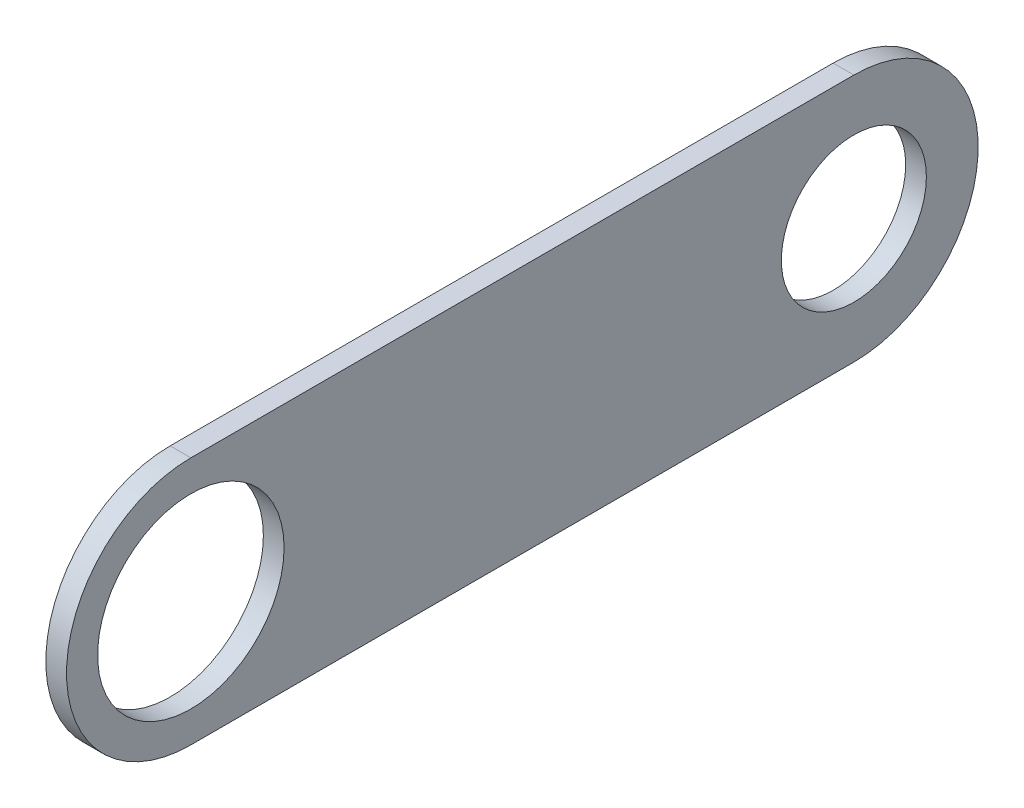
SolidWorks part; units mm, degrees
ref_plane "Front" through (0, 0, 0) normal (0, 0, 1) x (1, 0, 0)
ref_plane "Top" through (0, 0, 0) normal (0, 1, 0) x (1, 0, 0)
ref_plane "Right" through (0, 0, 0) normal (1, 0, 0) x (0, 0, -1)
sketch "Sketch1" plane through (0, 0, 0) normal (1, 0, 0) x (0, 0, -1)
  line L0 (-50.8, 0) -> (50.8, 0) construction
  line L1 (-50.8, 19.05) -> (50.8, 19.05)
  line L2 (-50.8, -19.05) -> (50.8, -19.05)
  arc A0 (-50.8, 19.05) -> (-50.8, -19.05) centre (-50.8, 0) ccw
  arc A1 (50.8, -19.05) -> (50.8, 19.05) centre (50.8, 0) ccw
  circle A2 centre (-50.8, 0) radius 14.2875
  circle A3 centre (50.8, 0) radius 11.1125
  point P2 (0, 0)
  dimension "D1" = 28.575
  dimension "D2" = 4.7625
  dimension "D4" = 22.225
  dimension "D3" = 101.6
extrude "Boss-Extrude1" add sketch "Sketch1" along normal blind 3.175
